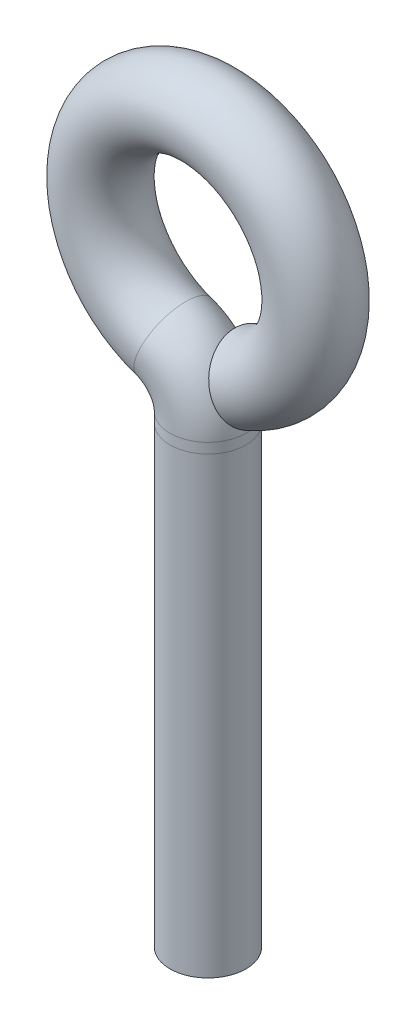
SolidWorks part; units mm, degrees
ref_plane "Front Plane" through (0, 0, 0) normal (0, 0, 1) x (1, 0, 0)
ref_plane "Top Plane" through (0, 0, 0) normal (0, 1, 0) x (1, 0, 0)
ref_plane "Right Plane" through (0, 0, 0) normal (1, 0, 0) x (0, 0, -1)
sketch "Sketch1" plane through (0, 0, 0) normal (0, 0, 1) x (1, 0, 0)
  line L0 (0, 0) -> (0, 18.215)
  line L3 (0, 18.215) -> (0, 18.6219)
  arc A1 (1.6613, 20.6524) -> (-1.3818, 20.5471) centre (0, 24.638) ccw
  arc A3 (0, 18.6219) -> (-1.3818, 20.5471) centre (-2.032, 18.6219) ccw
  dimension "D1" = 2.032
sweep "Sweep1" add path "Sketch1" circular profile diameter 3.048 parameters "D3"=3.048
